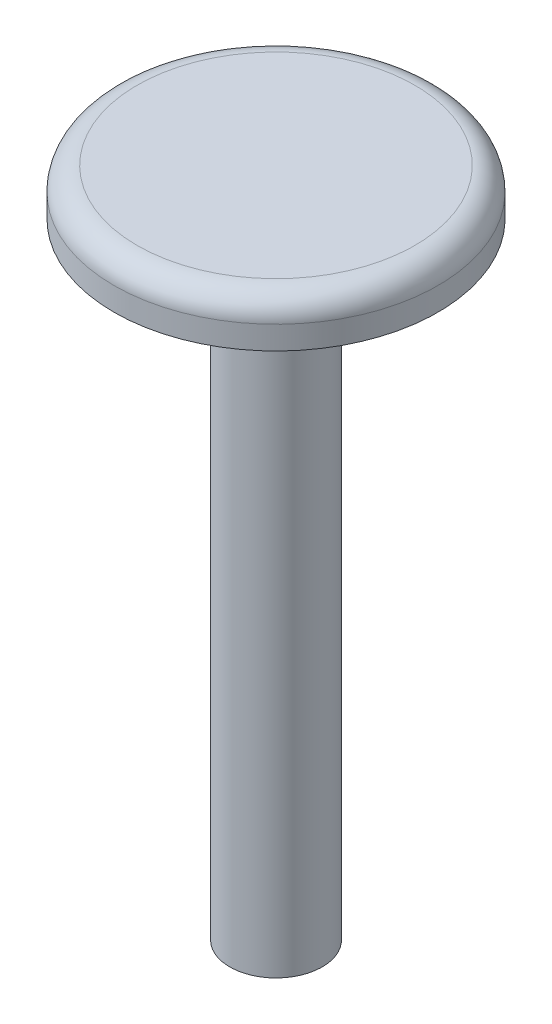
SolidWorks part; units mm, degrees
ref_plane "Front Plane" through (0, 0, 0) normal (0, 0, 1) x (1, 0, 0)
ref_plane "Top Plane" through (0, 0, 0) normal (0, 1, 0) x (1, 0, 0)
ref_plane "Right Plane" through (0, 0, 0) normal (1, 0, 0) x (0, 0, -1)
sketch "Sketch1" plane through (0, 0, 0) normal (0, 1, 0) x (1, 0, 0)
  circle A0 centre (0, 0) radius 35
  dimension "D1" = 70
extrude "Boss-Extrude1" add sketch "Sketch1" along normal blind 10
sketch "Sketch2" plane through (0, 0, 0) normal (0, -1, 0) x (1, 0, 0)
  circle A0 centre (0, 0) radius 10
  dimension "D1" = 20
extrude "Boss-Extrude2" add sketch "Sketch2" along normal blind 135
fillet "Fillet1" radius 5 1 edges at (0, 10, 35)
